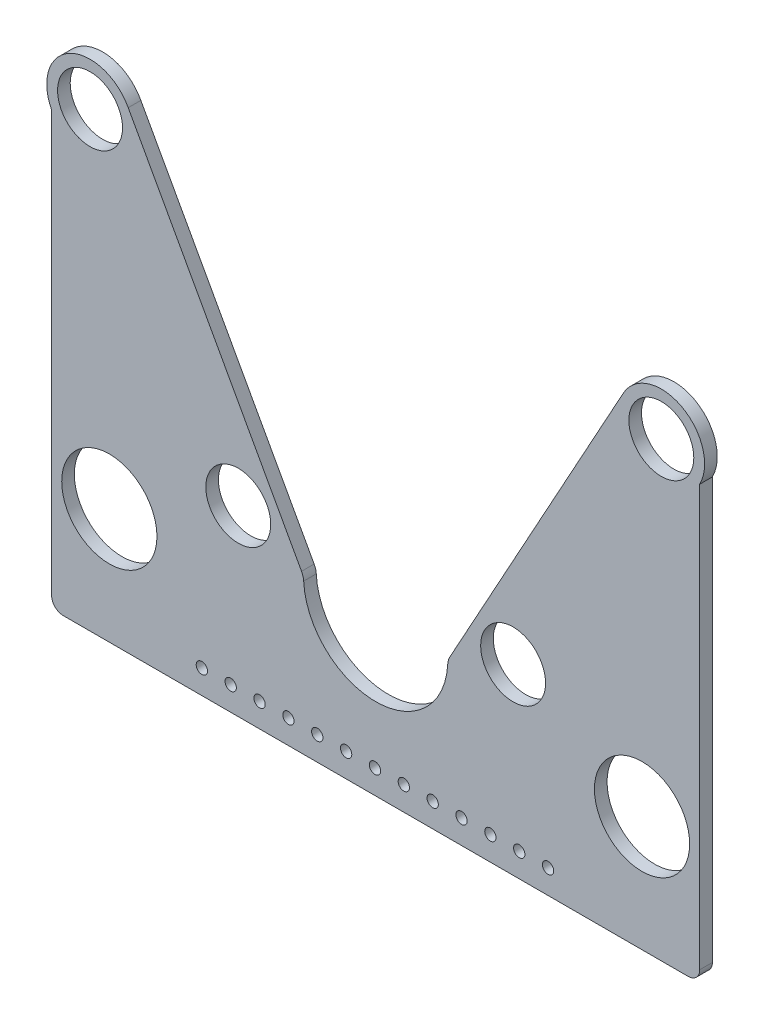
SolidWorks part; units mm, degrees
ref_plane "Front Plane" through (0, 0, 0) normal (0, 0, 1) x (1, 0, 0)
ref_plane "Top Plane" through (0, 0, 0) normal (0, 1, 0) x (1, 0, 0)
ref_plane "Right Plane" through (0, 0, 0) normal (1, 0, 0) x (0, 0, -1)
sketch "Sketch2" plane through (0, 0, 0) normal (0, 0, 1) x (1, 0, 0)
  line L0 (-106.68, -1076.9295) -> (-106.68, 48923.0705) construction
  line L1 (142.6324, 122.4629) -> (142.6324, -29.9371)
  line L2 (106.68, -1098.4025) -> (106.68, 48901.5975) construction
  line L3 (31.75, 0) -> (108.9183, 140.209)
  line L4 (0, -1082.0685) -> (0, 48917.9315) construction
  line L5 (-106.68, -44.45) -> (106.68, -44.45) construction
  line L8 (106.68, -55.9582) -> (106.68, -31.75)
  line L9 (-31.75, 0) -> (-108.9183, 140.209)
  line L10 (31.75, 0) -> (108.9183, 140.209)
  line L22 (-142.6324, -56.7419) -> (-142.6324, -62.6205)
  line L33 (-106.5644, -31.75) -> (0, -31.75) construction
  line L34 (-142.6324, 122.4629) -> (-142.6324, -29.9371)
  line L36 (-261.1394, 46.2048) -> (-243.4617, 46.2048) construction
  line L37 (-243.4617, 46.2048) -> (-243.4617, 28.5272) construction
  line L41 (-238.3305, 62.766) -> (-266.2705, 62.766) construction
  line L42 (-233.2505, 57.686) -> (-233.2505, 17.046) construction
  line L43 (-261.1394, 46.2048) -> (-261.1394, 28.5272) construction
  line L44 (-261.1394, 28.5272) -> (-243.4617, 28.5272) construction
  line L45 (-238.3305, 11.966) -> (-266.2705, 11.966) construction
  line L46 (-271.3505, 57.686) -> (-271.3505, 17.046) construction
  line L47 (-233.2505, 62.766) -> (-271.3505, 11.966) construction
  line L48 (-125.73, 3.175) -> (-125.73, -22.225) construction
  line L49 (-1101.9372, -9.525) -> (48898.0628, -9.525) construction
  line L50 (-233.2505, 11.966) -> (-271.3505, 62.766) construction
  line L51 (-239.6005, 56.416) -> (-239.6005, 18.316) construction
  line L52 (-265.0005, 56.416) -> (-239.6005, 56.416) construction
  line L53 (-125.73, 3.175) -> (-106.68, 3.175) construction
  line L54 (-142.6324, -56.7419) -> (142.6324, -56.7419) construction
  line L55 (-142.6324, -29.9371) -> (-142.6324, -56.7419)
  line L56 (142.6324, -29.9371) -> (142.6324, -56.7419)
  line L57 (-137.5524, -67.7005) -> (137.5524, -67.7005)
  line L58 (142.6324, -62.6205) -> (142.6324, -56.7419)
  arc A0 (-31.75, 0) -> (31.75, 0) centre (0, 0) ccw
  arc A1 (-108.9183, 140.209) -> (-142.6324, 122.4629) centre (-125.7268, 131.2438) ccw
  circle A2 centre (-60.4845, 12.7) radius 14.2875
  arc A3 (31.75, 0) -> (0, 31.75) centre (0, 0) ccw construction
  arc A4 (0, 31.75) -> (-31.75, 0) centre (0, 0) ccw construction
  arc A5 (137.5524, -67.7005) -> (142.6324, -62.6205) centre (137.5524, -62.6205) ccw
  arc A6 (-142.6324, -62.6205) -> (-137.5524, -67.7005) centre (-137.5524, -62.6205) ccw
  circle A7 centre (-125.7268, 131.2438) radius 14.2875
  circle A9 centre (-60.4845, 12.7) radius 19.05 construction
  circle A10 centre (60.4845, 12.7) radius 19.05 construction
  arc A11 (108.9183, 140.209) -> (142.6324, 122.4629) centre (125.7268, 131.2438) cw
  circle A12 centre (125.7268, 131.2438) radius 14.2875
  arc A40 (-142.6324, 122.4629) -> (-108.9183, 140.209) centre (-125.7268, 131.2438) ccw construction
  arc A41 (142.6324, 122.4629) -> (108.9183, 140.209) centre (125.7268, 131.2438) cw construction
  circle A42 centre (60.4845, 12.7) radius 14.2875
  circle A44 centre (-76.5175, -57.15) radius 2.4892
  circle A45 centre (-63.8175, -57.15) radius 2.4892
  circle A46 centre (-51.1175, -57.15) radius 2.4892
  circle A47 centre (-38.4175, -57.15) radius 2.4892
  circle A48 centre (-25.7175, -57.15) radius 2.4892
  circle A49 centre (-13.0175, -57.15) radius 2.4892
  circle A50 centre (-0.3175, -57.15) radius 2.4892
  circle A51 centre (12.3825, -57.15) radius 2.4892
  circle A52 centre (25.0825, -57.15) radius 2.4892
  circle A53 centre (37.7825, -57.15) radius 2.4892
  circle A54 centre (50.4825, -57.15) radius 2.4892
  circle A55 centre (63.1825, -57.15) radius 2.4892
  circle A56 centre (75.8825, -57.15) radius 2.4892
  arc A100 (-260.1552, 27.7564) -> (-262.1235, 29.2979) centre (-261.1394, 28.5272) ccw construction
  arc A101 (-262.1235, 29.2979) -> (-260.1552, 27.7564) centre (-261.1394, 28.5272) ccw construction
  arc A102 (-244.4458, 29.2979) -> (-242.4776, 27.7564) centre (-243.4617, 28.5272) ccw construction
  arc A103 (-242.4776, 27.7564) -> (-244.4458, 29.2979) centre (-243.4617, 28.5272) ccw construction
  arc A104 (-242.4776, 45.4341) -> (-244.4458, 46.9756) centre (-243.4617, 46.2048) ccw construction
  arc A105 (-244.4458, 46.9756) -> (-242.4776, 45.4341) centre (-243.4617, 46.2048) ccw construction
  arc A106 (-262.1235, 46.9756) -> (-260.1552, 45.4341) centre (-261.1394, 46.2048) ccw construction
  arc A107 (-260.1552, 45.4341) -> (-262.1235, 46.9756) centre (-261.1394, 46.2048) ccw construction
  circle A108 centre (-252.3005, 37.366) radius 7.3172 construction
  circle A109 centre (-265.0005, 56.416) radius 3.175 construction
  circle A110 centre (-239.6005, 56.416) radius 3.175 construction
  circle A111 centre (-239.6005, 18.316) radius 3.175 construction
  circle A112 centre (-265.0005, 18.316) radius 3.175 construction
  arc A113 (-266.2705, 11.966) -> (-271.3505, 17.046) centre (-266.2705, 17.046) cw construction
  arc A114 (-233.2505, 17.046) -> (-238.3305, 11.966) centre (-238.3305, 17.046) cw construction
  arc A115 (-238.3305, 62.766) -> (-233.2505, 57.686) centre (-238.3305, 57.686) cw construction
  arc A116 (-266.2705, 62.766) -> (-271.3505, 57.686) centre (-266.2705, 57.686) ccw construction
  circle A128 centre (-117.2324, -16.9005) radius 20.955
  circle A129 centre (117.2324, -16.9005) radius 20.955
  point P82 (-117.2324, -16.9005)
  point P83 (106.68, -30.0086)
  point P97 (-106.68, -29.6005)
  point P98 (117.2324, -16.9005)
  point P154 (-125.73, -9.525)
  dimension "D7" = 131.2438
  dimension "D8" = 25.4
  dimension "D9" = 25.4
  dimension "D3" = 44.45
  dimension "D14" = 106.68
  dimension "D17" = 38.1
  dimension "D5" = 5.08
  dimension "D15" = 31.75
  dimension "D16" = 28.575
  dimension "D18" = 28.575
  dimension "D19" = 19.05
  dimension "D21" = 125.7268
  dimension "D33" = 6.35
  dimension "D35" = 8.8388
  dimension "D37" = 8.8388
  dimension "D42" = 36.068
  dimension "D34" = 6.35
  dimension "D36" = 1.25
  dimension "D38" = 5.08
  dimension "D11" = 50.8
  dimension "D12" = 50.8
  dimension "D13" = 41.91
  dimension "1,65" = 41.91
  dimension "D1" = 28.828
  dimension "D6" = 10.9586
  dimension "D10" = 35.9524
  dimension "D20" = 142.6324
  dimension "D25" = 152.4
  dimension "D26" = 12.7
  dimension "D32" = 6.35
  dimension "D29" = 17.6777
  dimension "D30" = 50.8
  dimension "D31" = 38.1
  dimension "D39" = 25.4
  dimension "D40" = 38.1
  dimension "D41" = 16.9024
extrude "Boss-Extrude1" add sketch "Sketch2" along normal blind 3.175
sketch "Sketch3" plane through (0, 0, 3.175) normal (0, 0, -1) x (-1, 0, 0)
  line L0 (-125.7268, 150.2938) -> (49874.2732, 150.2938) construction
  line L1 (-144.7768, 131.2438) -> (-144.7768, 50131.2438) construction
  point P4 (-144.7768, 150.2938)
fillet "Fillet2" radius 7.62 2 edges at (31.75, 0, 1.5875) (-31.75, 0, 1.5875)
sketch "Sketch4" plane through (0, 0, 0) normal (0, 0, -1) x (-1, 0, 0)
  line L5 (-32.6406, 1.6181) -> (-108.9183, 140.209)
  line L6 (-142.6324, 122.4629) -> (-142.6324, -62.6205)
  line L7 (-137.5524, -67.7005) -> (137.5524, -67.7005)
  line L8 (142.6324, -62.6205) -> (142.6324, 122.4629)
  line L9 (108.9183, 140.209) -> (32.6406, 1.6181)
  line L10 (-32.6406, 1.6181) -> (-108.9183, 140.209)
  line L11 (-142.6324, 122.4629) -> (-142.6324, -62.6205)
  line L12 (-137.5524, -67.7005) -> (137.5524, -67.7005)
  line L13 (142.6324, -62.6205) -> (142.6324, 122.4629)
  line L14 (108.9183, 140.209) -> (32.6406, 1.6181)
  circle A0 centre (-75.8825, -57.15) radius 2.4892 construction
  circle A1 centre (-63.1825, -57.15) radius 2.4892 construction
  circle A2 centre (-50.4825, -57.15) radius 2.4892 construction
  circle A3 centre (-37.7825, -57.15) radius 2.4892 construction
  circle A4 centre (-25.0825, -57.15) radius 2.4892 construction
  circle A5 centre (-12.3825, -57.15) radius 2.4892 construction
  circle A6 centre (0.3175, -57.15) radius 2.4892 construction
  arc A7 (-31.7067, -1.6581) -> (31.7067, -1.6581) centre (0, 0) ccw
  arc A8 (-31.7067, -1.6581) -> (-32.6406, 1.6181) centre (-39.3163, -2.056) ccw
  arc A9 (-108.9183, 140.209) -> (-142.6324, 122.4629) centre (-125.7268, 131.2438) ccw
  arc A10 (-142.6324, -62.6205) -> (-137.5524, -67.7005) centre (-137.5524, -62.6205) ccw
  arc A11 (137.5524, -67.7005) -> (142.6324, -62.6205) centre (137.5524, -62.6205) ccw
  arc A12 (142.6324, 122.4629) -> (108.9183, 140.209) centre (125.7268, 131.2438) ccw
  arc A13 (32.6406, 1.6181) -> (31.7067, -1.6581) centre (39.3163, -2.056) ccw
  arc A14 (-31.7067, -1.6581) -> (31.7067, -1.6581) centre (0, 0) ccw
  arc A15 (-31.7067, -1.6581) -> (-32.6406, 1.6181) centre (-39.3163, -2.056) ccw
  arc A16 (-108.9183, 140.209) -> (-142.6324, 122.4629) centre (-125.7268, 131.2438) ccw
  arc A17 (-142.6324, -62.6205) -> (-137.5524, -67.7005) centre (-137.5524, -62.6205) ccw
  arc A18 (137.5524, -67.7005) -> (142.6324, -62.6205) centre (137.5524, -62.6205) ccw
  arc A19 (142.6324, 122.4629) -> (108.9183, 140.209) centre (125.7268, 131.2438) ccw
  arc A20 (32.6406, 1.6181) -> (31.7067, -1.6581) centre (39.3163, -2.056) ccw
  circle A21 centre (13.0175, -57.15) radius 2.4892 construction
  circle A22 centre (25.7175, -57.15) radius 2.4892 construction
  circle A23 centre (38.4175, -57.15) radius 2.4892 construction
  circle A24 centre (51.1175, -57.15) radius 2.4892 construction
  circle A25 centre (63.8175, -57.15) radius 2.4892 construction
  circle A26 centre (76.5175, -57.15) radius 2.4892 construction
  circle A27 centre (125.7268, 131.2438) radius 14.2875 construction
  circle A28 centre (117.2324, -16.9005) radius 20.955 construction
  circle A29 centre (60.4845, 12.7) radius 14.2875 construction
  circle A30 centre (-60.4845, 12.7) radius 14.2875 construction
  circle A31 centre (-117.2324, -16.9005) radius 20.955 construction
  circle A32 centre (-125.7268, 131.2438) radius 14.2875 construction
  circle A33 centre (-75.8825, -57.15) radius 2.4892
  circle A34 centre (-63.1825, -57.15) radius 2.4892
  circle A35 centre (-50.4825, -57.15) radius 2.4892
  circle A36 centre (-37.7825, -57.15) radius 2.4892
  circle A37 centre (-25.0825, -57.15) radius 2.4892
  circle A38 centre (-12.3825, -57.15) radius 2.4892
  circle A39 centre (0.3175, -57.15) radius 2.4892
  circle A40 centre (13.0175, -57.15) radius 2.4892
  circle A41 centre (25.7175, -57.15) radius 2.4892
  circle A42 centre (38.4175, -57.15) radius 2.4892
  circle A43 centre (51.1175, -57.15) radius 2.4892
  circle A44 centre (63.8175, -57.15) radius 2.4892
  circle A45 centre (76.5175, -57.15) radius 2.4892
  circle A46 centre (125.7268, 131.2438) radius 14.2875
  circle A47 centre (117.2324, -16.9005) radius 20.955
  circle A48 centre (60.4845, 12.7) radius 14.2875
  circle A49 centre (-60.4845, 12.7) radius 14.2875
  circle A50 centre (-117.2324, -16.9005) radius 20.955
  circle A51 centre (-125.7268, 131.2438) radius 14.2875
  dimension "D1" = 0
extrude "Boss-Extrude2" add sketch "Sketch4" along normal blind 2.3813
